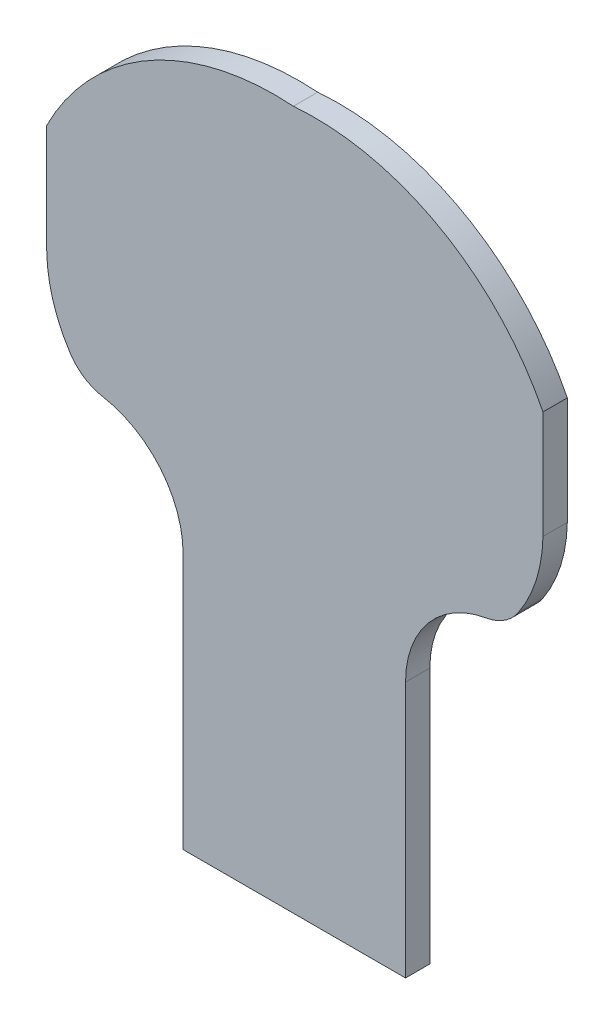
SolidWorks part; units mm, degrees
ref_plane "Спереди" through (0, 0, 0) normal (0, 0, 1) x (1, 0, 0)
ref_plane "Сверху" through (0, 0, 0) normal (0, 1, 0) x (1, 0, 0)
ref_plane "Справа" through (0, 0, 0) normal (1, 0, 0) x (0, 0, -1)
sketch "Эскиз1" plane through (0, 0, 0) normal (0, 0, 1) x (1, 0, 0)
  line L0 (29.1233, 63.4796) -> (68.8158, 63.4796) construction
  line L1 (51.0512, 63.4796) -> (51.0512, 85.6506)
  line L2 (-50.9488, 85.6506) -> (-50.9488, 63.4796)
  line L3 (-22.9109, -29.2324) -> (22.8017, -29.2324)
  line L4 (-0.2532, -199862.6946) -> (-0.2532, 200167.6633) construction
  line L7 (-22.9109, 23.4364) -> (-22.9109, -29.2324)
  line L9 (22.8017, 23.4364) -> (22.8017, -29.2324)
  arc A0 (-22.9109, 23.4364) -> (-39.466, 43.1375) centre (-42.9109, 23.4364) ccw
  arc A1 (39.4018, 43.1453) -> (22.8017, 23.4364) centre (42.8017, 23.4364) ccw
  arc A2 (-39.466, 43.1375) -> (-46.1137, 47.5161) centre (-37.7436, 52.9881) cw
  arc A3 (-50.9488, 63.4796) -> (-46.1137, 47.5161) centre (-21.2781, 63.7525) ccw
  arc A4 (51.0512, 63.4796) -> (46.0058, 47.428) centre (21.279, 64.0191) cw
  arc A5 (46.0058, 47.428) -> (39.4018, 43.1453) centre (37.7018, 52.9998) cw
  arc A6 (-50.9488, 85.6506) -> (-0.2532, 114.4085) centre (-4.0434, 62.027) cw
  arc A7 (51.0512, 85.6506) -> (-0.2532, 114.4085) centre (4.1229, 62.0727) ccw
  point P0 (0, 0)
  point P14 (-23.267, 44.4248)
  point P17 (23.1578, 44.4248)
  point P20 (-50.9488, 44.4248)
  point P23 (51.0512, 44.4248)
  dimension "D1" = 20
  dimension "D2" = 10
extrude "Вытянуть1" add sketch "Эскиз1" along normal blind 5
sketch "Эскиз2" plane through (0, 0, 0) normal (0, 0, 1) x (1, 0, 0)
  line L0 (0, 27.6566) -> (0, -11.0597) construction
